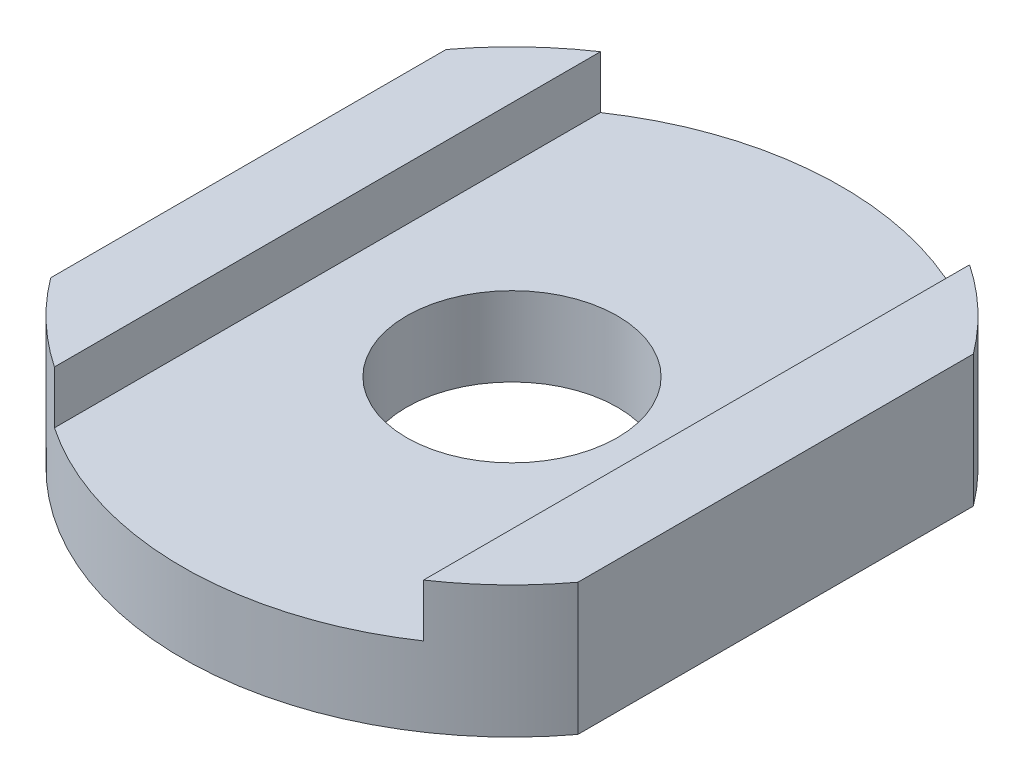
SolidWorks part; units mm, degrees
ref_plane "Płaszczyzna przednia" through (0, 0, 0) normal (0, 0, 1) x (1, 0, 0)
ref_plane "Płaszczyzna górna" through (0, 0, 0) normal (0, 1, 0) x (1, 0, 0)
ref_plane "Płaszczyzna prawa" through (0, 0, 0) normal (1, 0, 0) x (0, 0, -1)
sketch "Szkic1" plane through (0, 0, 0) normal (0, 1, 0) x (1, 0, 0)
  line L0 (-10, 7.5) -> (-10, -7.5)
  line L1 (10, 7.5) -> (10, -7.5)
  circle A0 centre (0, 0) radius 4
  arc A1 (-10, -7.5) -> (10, -7.5) centre (0, 0) ccw
  arc A2 (10, 7.5) -> (-10, 7.5) centre (0, 0) ccw
  point P8 (0, 0)
  point P9 (0, 0)
  point P10 (0, 0)
  point P11 (0, 0)
  dimension "D1" = 8
  dimension "D2" = 25
  dimension "D3" = 10
extrude "Dodanie-wyciągnięcie1" add sketch "Szkic1" along normal blind 3
sketch "Szkic2" plane through (0, 3, 0) normal (0, 1, 0) x (1, 0, 0)
  line L0 (-10, -7.5) -> (-10, 7.5)
  line L1 (-7, 10.3562) -> (-7, -10.3562)
  line L2 (7, 10.3562) -> (7, -10.3562)
  line L3 (10, 7.5) -> (10, -7.5)
  arc A0 (10, 7.5) -> (-10, 7.5) centre (0, 0) ccw construction
  arc A1 (-10, -7.5) -> (10, -7.5) centre (0, 0) ccw construction
  arc A2 (10, 7.5) -> (-10, 7.5) centre (0, 0) ccw
  arc A3 (-10, -7.5) -> (10, -7.5) centre (0, 0) ccw
  point P6 (0, 0)
  point P7 (0, 0)
  arc M3 (10, 7.5) -> (-10, 7.5) centre (0, 0) ccw
  line M4 (-10, 7.5) -> (-10, -7.5)
  arc M5 (-10, -7.5) -> (10, -7.5) centre (0, 0) ccw
  line M6 (10, -7.5) -> (10, 7.5)
  dimension "D1" = 3
  dimension "D2" = 3
extrude "Dodanie-wyciągnięcie2" add sketch "Szkic2" along normal blind 2 contours L1 M3 M4 M5 | L2 M3 M5 M6
